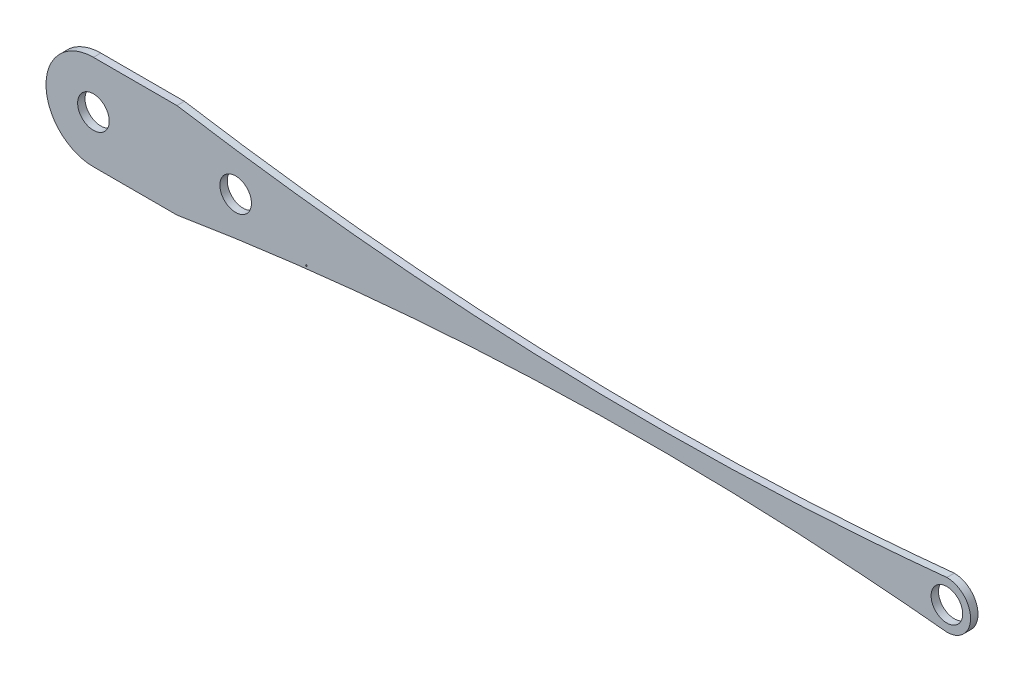
SolidWorks part; units mm, degrees
ref_plane "Front Plane" through (0, 0, 0) normal (0, 0, 1) x (1, 0, 0)
ref_plane "Top Plane" through (0, 0, 0) normal (0, 1, 0) x (1, 0, 0)
ref_plane "Right Plane" through (0, 0, 0) normal (1, 0, 0) x (0, 0, -1)
sketch "Sketch4" plane through (0, 0, 0) normal (0, 0, 1) x (1, 0, 0)
  line L0 (0, 0) -> (457.2, 0) construction
  line L1 (0, 25.4) -> (44.7423, 25.4)
  line L2 (0, -25.4) -> (44.7423, -25.4)
  arc A0 (0, 25.4) -> (0, -25.4) centre (0, 0) ccw
  circle A2 centre (0, 0) radius 8.4667
  circle A3 centre (76.2, 0) radius 8.4667
  circle A4 centre (457.2, 0) radius 8.4667
  arc A5 (457.2, -12.7) -> (457.2, 12.7) centre (457.2, 0) ccw
  arc A6 (44.7423, 25.4) -> (52.6769, 24.1289) centre (44.7423, 0) cw
  arc A7 (52.6769, -24.1289) -> (44.7423, -25.4) centre (44.7423, 0) cw
  spline S0 degree 2 poles (44.7423, 25.4) (249.9499, -8.0007) (457.2, 12.7) knots 0 0 0 1 1 1
  spline S1 degree 2 poles (44.7423, -25.4) (249.9499, 8.0007) (457.2, -12.7) knots 0 0 0 1 1 1
  point P3 (228.6, 0)
  dimension "D3" = 16.9333
  dimension "D5" = 25.4
  dimension "D1" = 50.8
  dimension "D2" = 457.2
  dimension "D6" = 19.05
  dimension "D7" = 19.05
  dimension "D8" = 76.2
extrude "Boss-Extrude2" add sketch "Sketch4" along normal blind 3.9688
scale "Scale1" scale about centroid uniform scaling yes scale factor 0.75
sketch "Sketch5" plane through (0, 0, 3.4727) normal (0, 0, 1) x (1, 0, 0)
  circle A0 centre (124.9402, -10.6445) radius 0.2857
  point P2 (123.246, -10.7126)
  point P3 (124.9402, -10.6445)
  dimension "D1" = 0.5715
extrude "Cut-Extrude1" cut sketch "Sketch5" against normal through all both
